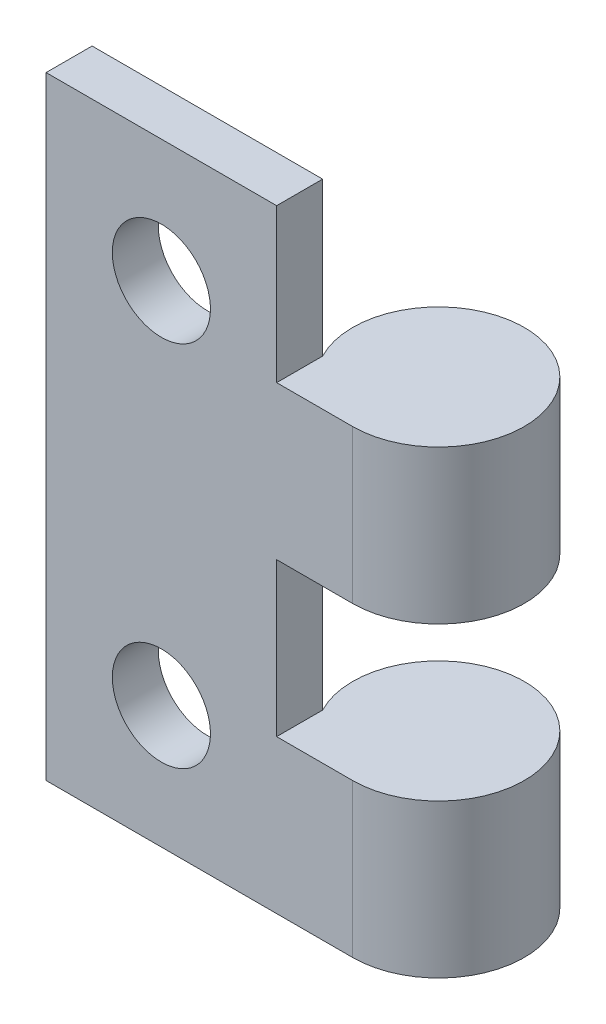
SolidWorks part; units mm, degrees
ref_plane "前视基准面" through (0, 0, 0) normal (0, 0, 1) x (1, 0, 0)
ref_plane "上视基准面" through (0, 0, 0) normal (0, 1, 0) x (1, 0, 0)
ref_plane "右视基准面" through (0, 0, 0) normal (1, 0, 0) x (0, 0, -1)
other "Configuration Table"
sketch "草图1" plane through (0, 0, 0) normal (0, 1, 0) x (1, 0, 0)
  line L1 (-5, -0.75) -> (5, -0.75)
  line L2 (-5, -0.75) -> (-5, 0.75)
  line L3 (-5, 0.75) -> (5, 0.75)
  line L4 (5, -0.75) -> (5, 0.75)
  line L5 (-5, -0.75) -> (5, 0.75) construction
  line L6 (-5, 0.75) -> (5, -0.75) construction
  circle A0 centre (5, 2.05) radius 2.8
  point P0 (0, 0)
extrude "凸台-拉伸2" add sketch "草图1" along normal blind 20 contours L4 A0 L3 | L3 A0 L4 | A0 L3 L2 L1
sketch "草图4" plane through (-5, 0, 0) normal (-1, 0, 0) x (0, 0, 1)
  line L0 (-4.85, 20) -> (-4.85, 0) construction
  line L1 (-0.75, 20) -> (-4.85, 20)
  line L2 (-0.75, 20) -> (-0.75, 15)
  line L3 (-0.75, 15) -> (-4.85, 15)
  line L4 (-4.85, 20) -> (-4.85, 15)
  line L6 (-0.75, 15) -> (-4.85, 15)
  line L7 (-0.75, 15) -> (-0.75, 10)
  line L8 (-0.75, 10) -> (-4.85, 10)
  line L9 (-4.85, 15) -> (-4.85, 10)
  line L10 (-0.75, 10) -> (-4.85, 10)
  line L11 (-0.75, 10) -> (-0.75, 5)
  line L12 (-0.75, 5) -> (-4.85, 5)
  line L13 (-4.85, 10) -> (-4.85, 5)
  line L14 (-0.75, 5) -> (-4.85, 5)
  line L15 (-0.75, 5) -> (-0.75, 0)
  line L16 (-0.75, 0) -> (-4.85, 0)
  line L17 (-4.85, 5) -> (-4.85, 0)
  line M20 (-0.75, 20) -> (-0.75, 0)
extrude "切除-拉伸1" cut sketch "草图4" against normal blind 23 contours L1 L4 L3 M20 | L8 L13 L12 M20
sketch "草图5" plane through (0, 0, -0.75) normal (0, 0, -1) x (-1, 0, 0)
  line L0 (-2.2, 5) -> (-7.8, 5) construction
  line L1 (-2.5201, 10) -> (-7.4799, 10)
  line L2 (-2.5201, 10) -> (-2.5201, 5)
  line L3 (-2.5201, 5) -> (-7.4799, 5)
  line L4 (-7.4799, 10) -> (-7.4799, 5)
  line L5 (-7.4799, 10) -> (-7.4799, 5) construction
  line L7 (-2.5201, 15) -> (-7.4799, 15)
  line L8 (-2.5201, 15) -> (-2.5201, 20)
  line L9 (-2.5201, 20) -> (-7.4799, 20)
  line L10 (-7.4799, 15) -> (-7.4799, 20)
extrude "切除-拉伸2" cut sketch "草图5" against normal blind 23 contours L2 L1 L4 L3 | L8 L7 L10 L9
sketch "草图6" plane through (0, 0, -0.75) normal (0, 0, -1) x (-1, 0, 0)
  line L3 (1.24, 4) -> (1.24, 16)
  circle A0 centre (1.24, 16) radius 1.6
  circle A1 centre (1.24, 4) radius 1.6
  point P9 (1.24, 10)
extrude "切除-拉伸3" cut sketch "草图6" against normal blind 23
